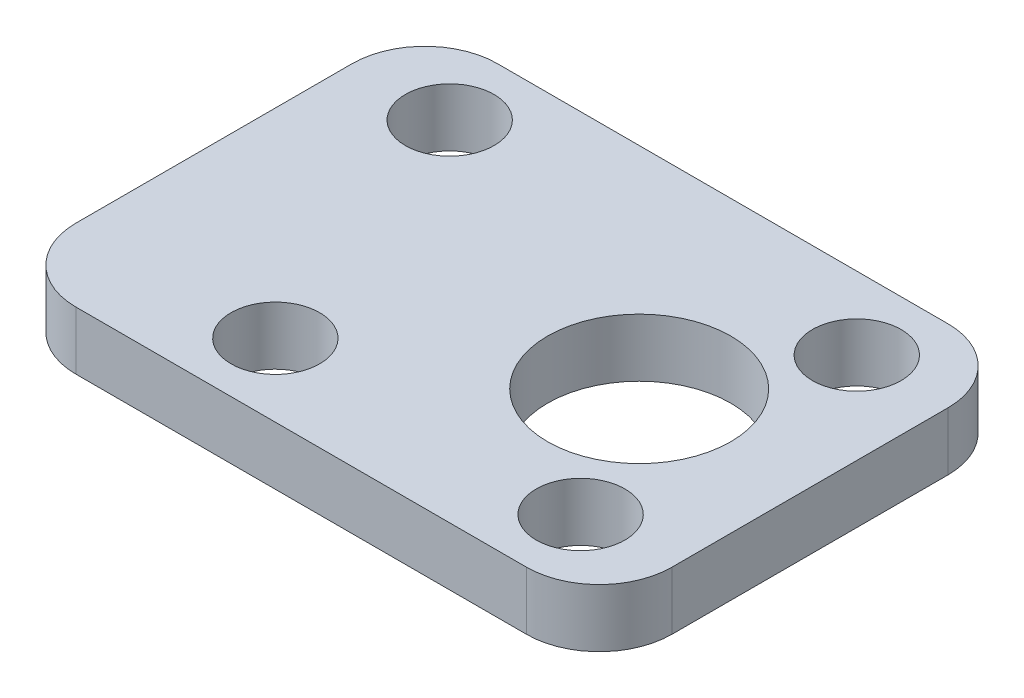
SolidWorks part; units mm, degrees
ref_plane "Front Plane" through (0, 0, 0) normal (0, 0, 1) x (1, 0, 0)
ref_plane "Top Plane" through (0, 0, 0) normal (0, 1, 0) x (1, 0, 0)
ref_plane "Right Plane" through (0, 0, 0) normal (1, 0, 0) x (0, 0, -1)
sketch "Sketch1" plane through (0, 0, 0) normal (0, 1, 0) x (1, 0, 0)
  line L1 (0, 0) -> (82, 0)
  line L2 (0, 0) -> (0, 58)
  line L3 (0, 58) -> (82, 58)
  line L4 (82, 0) -> (82, 58)
  line L5 (0, 58) -> (82, 58) construction
  line L6 (0, 58) -> (0, 118.9)
  line L7 (0, 29) -> (82, 29) construction
  line L8 (0, 118.9) -> (82, 118.9)
  line L9 (0, 48) -> (82, 48) construction
  line L10 (82, 58) -> (82, 118.9)
  line L11 (0, 10) -> (82, 10) construction
  circle A4 centre (12.5611, 48) radius 6.1
  circle A5 centre (12.5611, 10) radius 6.1
  circle A6 centre (54.5611, 10) radius 6.1
  circle A7 centre (68.57, 48) radius 6.1
  circle A8 centre (23.5, 29) radius 12.6
  dimension "D10" = 12.2
  dimension "D12" = 42
  dimension "D13" = 40.5
  dimension "D14" = 25.2
  dimension "D15" = 23.5
  dimension "D16" = 45.07
  dimension "D1" = 58
  dimension "D2" = 82
  dimension "D3" = 60.9
  dimension "D8" = 38
  dimension "D9" = 19
extrude "Boss-Extrude1" add sketch "Sketch1" along normal blind 8 contours L1 L4 L3 L2 A8 A7 A6 A5 A4
fillet "Fillet1" radius 10 4 edges at (82, 4, 0) (0, 4, 0) (0, 4, -58) (82, 4, -58)
mirror "Mirror1" about plane through (82, 8, 0) normal (-1, 0, 0) of "Fillet1", "Boss-Extrude1"
sketch "Sketch2" plane through (0, 8, 0) normal (0, 1, 0) x (1, 0, 0)
  line L0 (10, 58) -> (72, 58) construction
  line L1 (0, 0) -> (82, 0)
  line L2 (0, 0) -> (0, 58)
  line L3 (0, 58) -> (82, 58)
  line L4 (82, 0) -> (82, 58)
extrude "Cut-Extrude1" cut sketch "Sketch2" against normal through all
